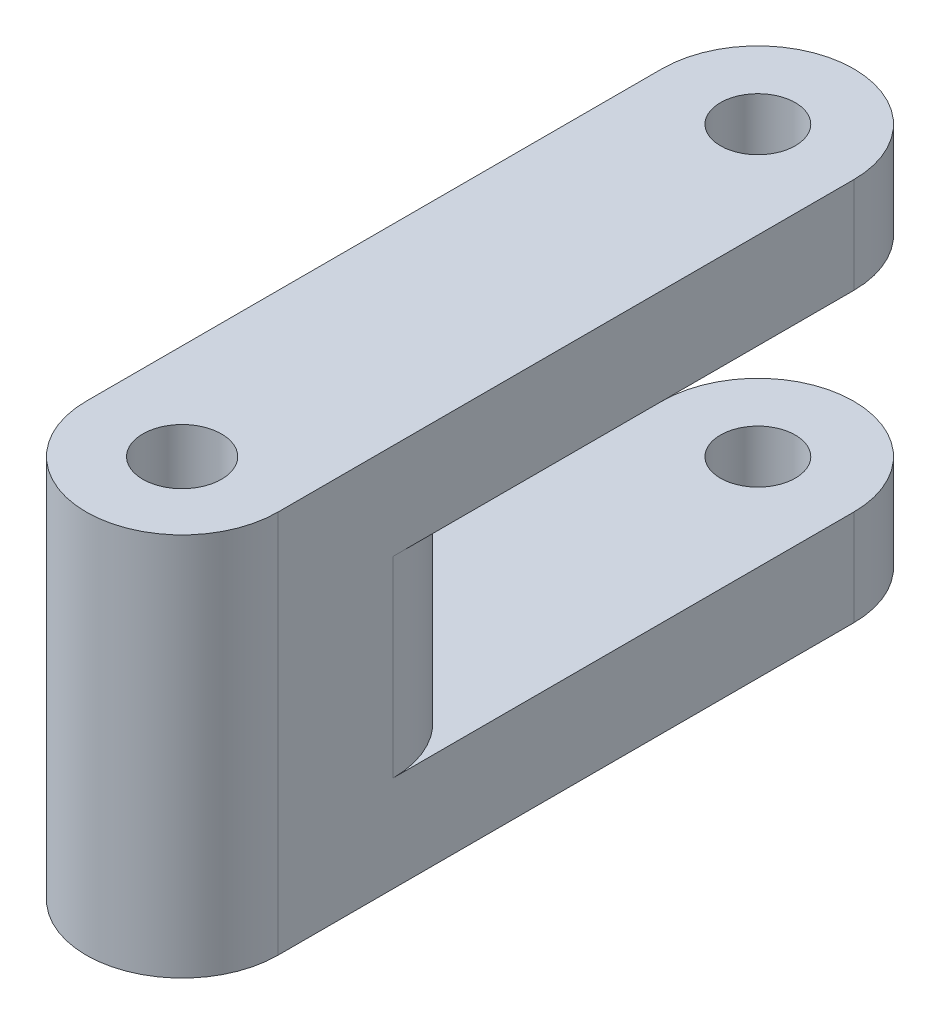
SolidWorks part; units mm, degrees
ref_plane "Plan de face" through (0, 0, 0) normal (0, 0, 1) x (1, 0, 0)
ref_plane "Plan de dessus" through (0, 0, 0) normal (0, 1, 0) x (1, 0, 0)
ref_plane "Plan de droite" through (0, 0, 0) normal (1, 0, 0) x (0, 0, -1)
sketch "Esquisse1" plane through (0, 0, 0) normal (0, 1, 0) x (1, 0, 0)
  line L0 (0, 0) -> (0, 30) construction
  line L1 (-5, 0) -> (-5, 30)
  line L2 (5, 0) -> (5, 30)
  arc A0 (-5, 0) -> (5, 0) centre (0, 0) ccw
  arc A1 (5, 30) -> (-5, 30) centre (0, 30) ccw
  circle A2 centre (0, 30) radius 1.95
  circle A3 centre (0, 0) radius 2.05
  point P3 (0, 15)
  dimension "D3" = 4.1
  dimension "D4" = 3.9
  dimension "D1" = 10
  dimension "D2" = 30
extrude "Boss.-Extru.1" add sketch "Esquisse1" along normal blind 5
sketch "Esquisse2" plane through (0, 5, 0) normal (0, 1, 0) x (1, 0, 0)
  line L0 (0, 0) -> (0, 6) construction
  line L1 (-5, 0) -> (-5, 6)
  line L2 (5, 0) -> (5, 6)
  arc A0 (-5, 0) -> (5, 0) centre (0, 0) ccw
  arc A1 (5, 6) -> (-5, 6) centre (0, 6) ccw
  arc A2 (-5, 0) -> (5, 0) centre (0, 0) ccw construction
  circle A3 centre (0, 0) radius 2.05 construction
  circle A4 centre (0, 0) radius 2.05
  point P3 (0, 3)
  dimension "D1" = 6
extrude "Boss.-Extru.2" add sketch "Esquisse2" along normal blind 10
sketch "Esquisse3" plane through (0, 5, 0) normal (0, 1, 0) x (1, 0, 0)
  line L0 (5, 0) -> (5, 6) construction
  line L1 (-5, 6) -> (-5, 0) construction
  line L2 (5, 6) -> (5, 30) construction
  line L3 (-5, 30) -> (-5, 6) construction
  line L4 (5, 0) -> (5, 6)
  line L5 (-5, 6) -> (-5, 0)
  line L6 (5, 6) -> (5, 30)
  line L7 (-5, 30) -> (-5, 6)
  arc A0 (-5, 0) -> (5, 0) centre (0, 0) ccw construction
  arc A1 (5, 6) -> (-5, 6) centre (0, 6) ccw construction
  arc A2 (5, 6) -> (-5, 6) centre (0, 6) ccw construction
  arc A3 (5, 30) -> (-5, 30) centre (0, 30) ccw construction
  arc A4 (-5, 0) -> (5, 0) centre (0, 0) ccw
  arc A5 (5, 6) -> (-5, 6) centre (0, 6) ccw
  arc A6 (5, 6) -> (-5, 6) centre (0, 6) ccw
  arc A7 (5, 30) -> (-5, 30) centre (0, 30) ccw
  circle A8 centre (0, 30) radius 1.95 construction
  circle A9 centre (0, 0) radius 2.05 construction
  circle A10 centre (0, 30) radius 1.95
  circle A11 centre (0, 0) radius 2.05
  arc M1 (-5, 6) -> (5, 6) centre (0, 6) cw
  line M2 (5, 6) -> (5, 30)
  arc M3 (5, 30) -> (-5, 30) centre (0, 30) ccw
  line M4 (-5, 30) -> (-5, 6)
  circle M5 centre (0, 30) radius 1.95
extrude "Boss.-Extru.3" add sketch "Esquisse3" along normal blind 5 from surface at 10 contours M4 M1 M2 M3 M5 | L5 A4 L4 A11 M1 starting at face at (0, 15, -3)
